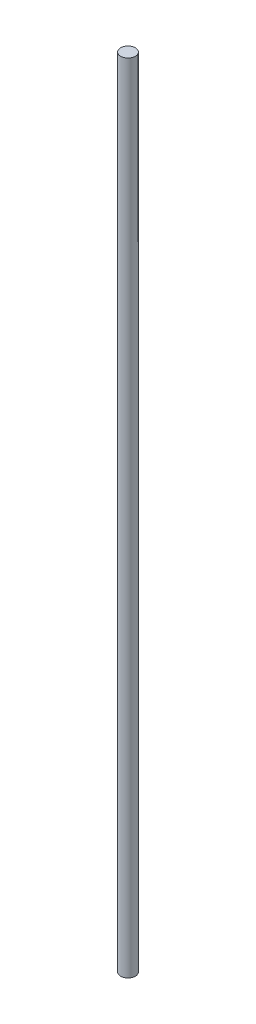
SolidWorks part; units mm, degrees
ref_plane "Front Plane" through (0, 0, 0) normal (0, 0, 1) x (1, 0, 0)
ref_plane "Top Plane" through (0, 0, 0) normal (0, 1, 0) x (1, 0, 0)
ref_plane "Right Plane" through (0, 0, 0) normal (1, 0, 0) x (0, 0, -1)
sketch "Sketch1" plane through (0, 0, 0) normal (0, 1, 0) x (1, 0, 0)
  circle A0 centre (0, 0) radius 3
  dimension "D1" = 6
extrude "Boss-Extrude1" add sketch "Sketch1" along normal blind 324.5
